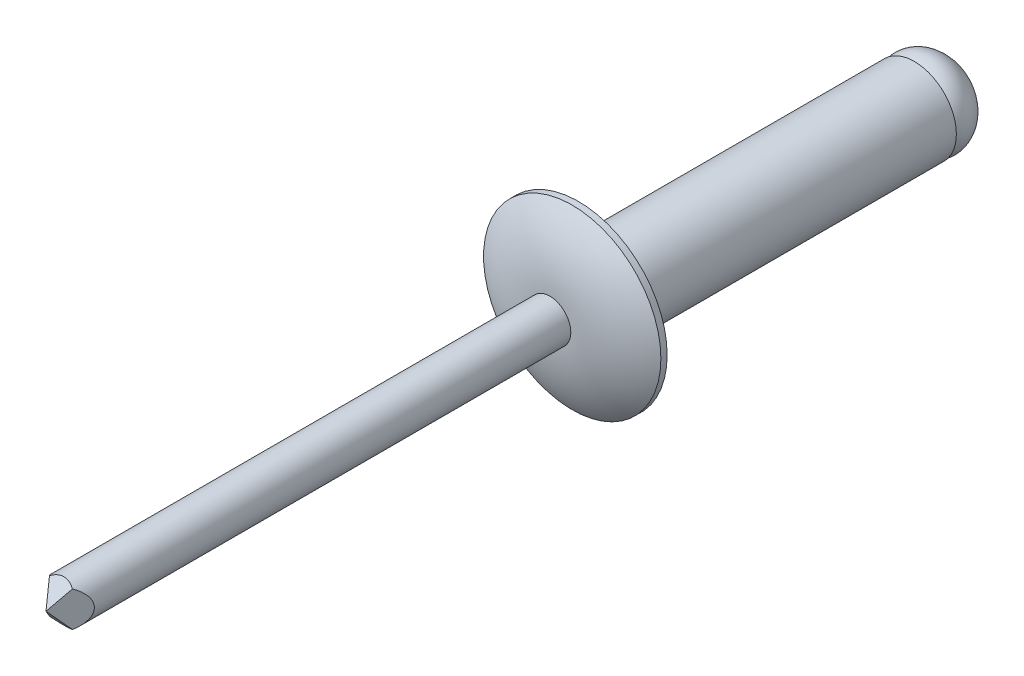
SolidWorks part; units mm, degrees
ref_plane "Front" through (0, 0, 0) normal (0, 0, 1) x (1, 0, 0)
ref_plane "Top" through (0, 0, 0) normal (0, 1, 0) x (1, 0, 0)
ref_plane "Right" through (0, 0, 0) normal (1, 0, 0) x (0, 0, -1)
sketch "layout" plane through (0, 0, 0) normal (1, 0, 0) x (0, 0, -1)
  line L0 (-15.1003, 0) -> (-0.8128, 0) construction
  line L1 (-0.8128, 0) -> (0, 0) construction
  line L2 (0, 0) -> (9.525, 0) construction
  line L3 (9.525, 0) -> (10.7442, 0) construction
  line L8 (0, 2.5146) -> (0, -2.5146) construction
  line L9 (9.525, 1.1906) -> (9.525, -1.1906) construction
  dimension "length" = 9.525
  dimension "Head Height" = 0.8128
  dimension "D5" = 1.2192
  dimension "Dia" = 2.3813
  dimension "D9" = 14.2875
  dimension "Head Diameter" = 5.0292
sketch "Sketch2" plane through (0, 0, 0) normal (1, 0, 0) x (0, 0, -1)
  line L0 (-15.1003, 0) -> (-15.1003, 0.5953)
  line L3 (0, 0) -> (0, 2.5146) construction
  line L4 (-0.8128, 0) -> (-0.8128, -1.8472) construction
  line L5 (9.525, 1.1906) -> (0, 1.1906)
  line L6 (9.525, 1.1906) -> (9.525, 0) construction
  line L7 (9.8298, 1.1906) -> (9.8298, -1.1906) construction
  line L8 (8.9154, 0) -> (9.525, 0) construction
  line L9 (10.7442, 0) -> (10.7442, 1.1906) construction
  line L10 (9.525, 1.1906) -> (9.8298, 1.1906) construction
  line L11 (9.8298, 1.1906) -> (10.1346, 1.1906) construction
  line L12 (-15.1003, 0) -> (9.525, 0)
  line L13 (-0.8128, 0.5953) -> (-0.8128, 0) construction
  line L14 (10.1346, 1.1906) -> (10.4394, 1.1906) construction
  line L15 (10.4394, 1.1906) -> (10.7442, 1.1906) construction
  line L16 (9.525, 1.1225) -> (9.525, 1.1906)
  line L17 (9.525, 1.1225) -> (9.525, 0) construction
  line L18 (9.525, 0) -> (10.7442, 0)
  line L19 (0, 1.1906) -> (0, 2.5146)
  line L20 (-0.8128, 0.5953) -> (-15.1003, 0.5953)
  line L22 (0, 2.5146) -> (-0.1778, 2.5146)
  arc A2 (-0.1778, 2.5146) -> (-0.8128, 0.5953) centre (2.4052, 0.5953) ccw
  ellipse E0 centre (9.8298, 0) end of major axis (9.8298, -1.1906) minor radius 0.9144 (10.7442, 0) -> (9.525, 1.1225) ccw
  dimension "D1" = 0.1778
  dimension "D2" = 1.1906
  dimension "D3" = 0.5953
revolve "Revolve1" add sketch "Sketch2" angle 360 about L12
sketch "Sketch3" plane through (0, 0, 0) normal (0, 1, 0) x (1, 0, 0)
  line L0 (0, -15.1003) -> (0.7985, -14.0597)
  line L1 (-0.5953, -15.1003) -> (0.5953, -15.1003) construction
  line L3 (0, -15.1003) -> (0, -15.6083) construction
  line L4 (0, -15.1003) -> (-0.7985, -14.0597)
  line L5 (-0.7985, -14.0597) -> (-0.7985, -15.6083)
  line L6 (-0.7985, -15.6083) -> (0.7985, -15.6083)
  line L7 (0.7985, -15.6083) -> (0.7985, -14.0597)
  dimension "D1" = 75
  dimension "D2" = 0.2032
  dimension "D3" = 0.508
extrude "Cut-Extrude1" cut sketch "Sketch3" against normal through all both and the other way through all
sketch "Sketch5" plane through (0, 0, 0) normal (1, 0, 0) x (0, 0, -1)
  line L0 (-15.1003, 0) -> (-14.3245, 0.9128)
  line L1 (-15.1003, -0.5953) -> (-15.1003, 0.5953) construction
  line L2 (-14.3245, 0.9128) -> (-15.4178, 0.9128)
  line L3 (-15.4178, 0.9128) -> (-15.4178, -0.9128)
  line L4 (-15.4178, -0.9128) -> (-14.3245, -0.9128)
  line L5 (-14.3245, -0.9128) -> (-15.1003, 0)
  line L6 (-15.1003, 0) -> (-9.2614, 0) construction
  line L7 (-0.8128, 0.5953) -> (-15.1003, 0.5953) construction
  line L8 (-14.3245, 0) -> (-14.3245, 0.9128) construction
  ellipse E0 centre (-15.1003, 0) end of major axis (-15.8761, 0) minor radius 0.5953 (-15.1003, -0.5953) -> (-15.1003, 0.5953) ccw construction
  dimension "D1" = 0.3175
  dimension "D2" = 0.3175
extrude "Cut-Extrude2" cut sketch "Sketch5" against normal through all both and the other way through all
fillet "Fillet2" [suppressed] radius 0.254
equation "\"D5@layout\"=\"Head Height@layout\"*1.5"
equation "\"D9@layout\"=\"length@layout\"*1.5"
equation "\"D2@Sketch5\"=\"D1@Sketch5\""
equation "\"D3@Sketch2\"=\"D2@Sketch2\"/2"
